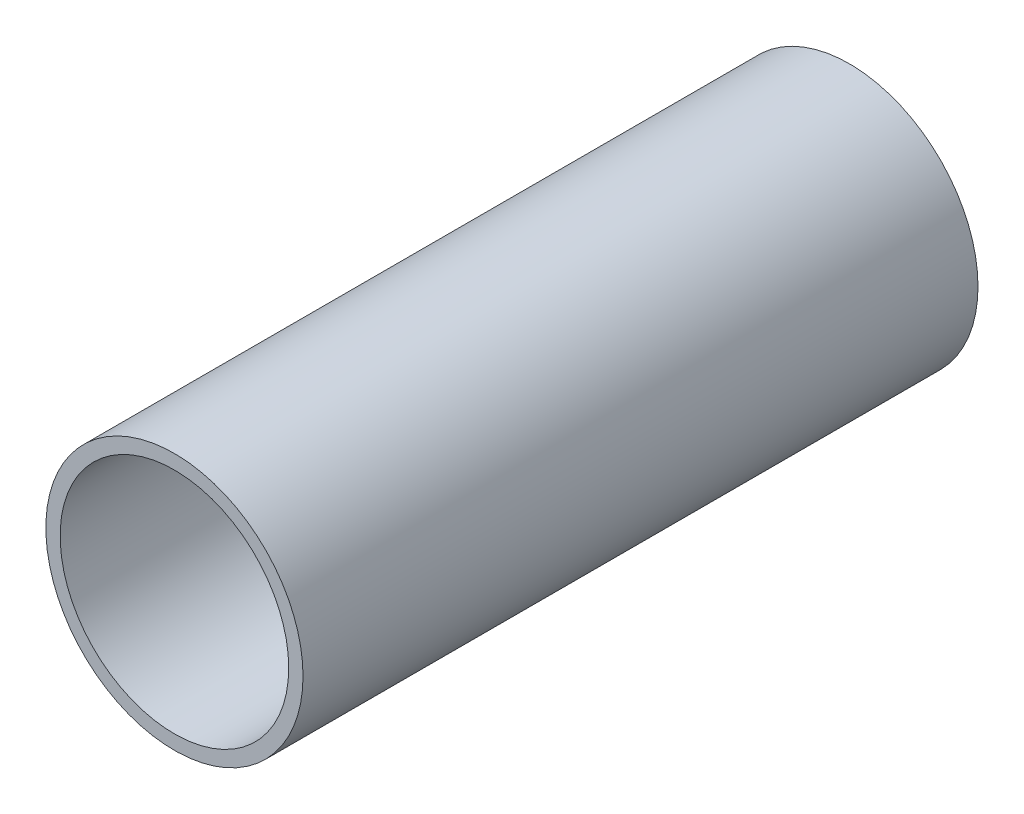
SolidWorks part; units mm, degrees
material "ｱｸﾘﾙ (中-上級の耐衝撃性)"
ref_plane "正面" through (0, 0, 0) normal (0, 0, 1) x (1, 0, 0)
ref_plane "平面" through (0, 0, 0) normal (0, 1, 0) x (1, 0, 0)
ref_plane "右側面" through (0, 0, 0) normal (1, 0, 0) x (0, 0, -1)
sketch "ｽｹｯﾁ1" plane through (0, 0, 0) normal (0, 0, 1) x (1, 0, 0)
  circle A0 centre (0, 0) radius 50.8
  circle A1 centre (0, 0) radius 57.15
  dimension "D1" = 101.6
  dimension "D2" = 114.3
extrude "ﾎﾞｽ - 押し出し1" add sketch "ｽｹｯﾁ1" along normal blind 300
